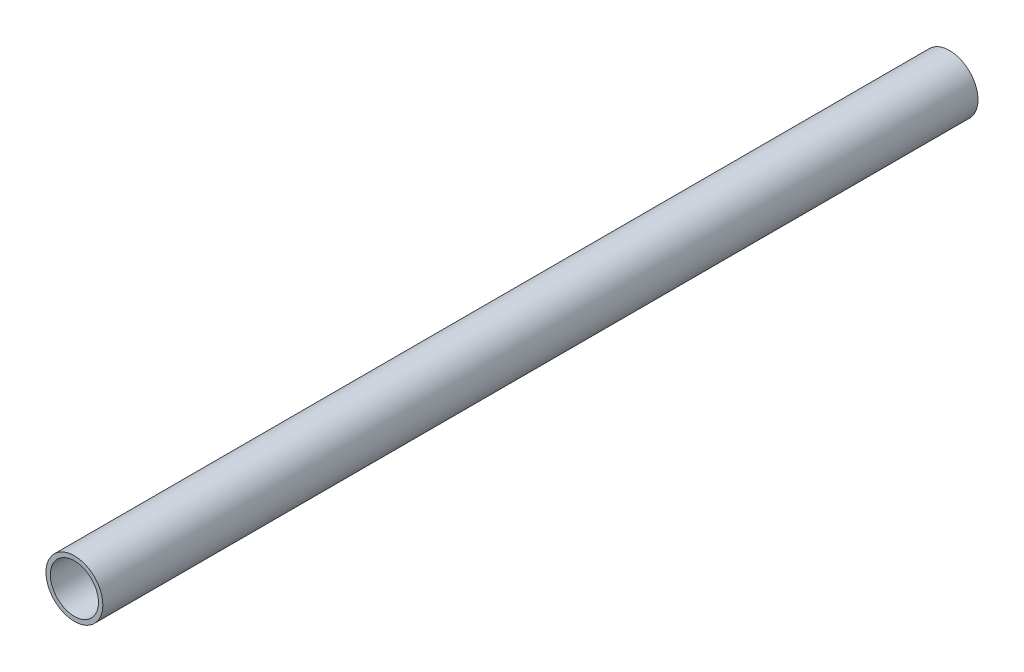
SolidWorks part; units mm, degrees
ref_plane "Front Plane" through (0, 0, 0) normal (0, 0, 1) x (1, 0, 0)
ref_plane "Top Plane" through (0, 0, 0) normal (0, 1, 0) x (1, 0, 0)
ref_plane "Right Plane" through (0, 0, 0) normal (1, 0, 0) x (0, 0, -1)
sketch "Sketch1" plane through (0, 0, 0) normal (0, 0, 1) x (1, 0, 0)
  circle A0 centre (0, 0) radius 6.5
  circle A1 centre (0, 0) radius 5.5
  dimension "D1" = 13
  dimension "D2" = 11
extrude "Boss-Extrude1" add sketch "Sketch1" along normal blind 200
